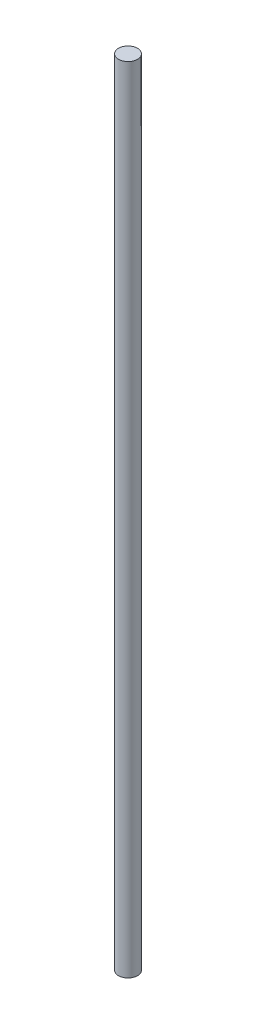
SolidWorks part; units mm, degrees
material "1.2343 (X38CrMoV5-1)"
ref_plane "Front Plane" through (0, 0, 0) normal (0, 0, 1) x (1, 0, 0)
ref_plane "Top Plane" through (0, 0, 0) normal (0, 1, 0) x (1, 0, 0)
ref_plane "Right Plane" through (0, 0, 0) normal (1, 0, 0) x (0, 0, -1)
sketch "Sketch1" plane through (0, 0, 0) normal (0, 1, 0) x (1, 0, 0)
  circle A0 centre (0, 0) radius 5
  dimension "D1" = 10
extrude "Boss-Extrude1" add sketch "Sketch1" along normal blind 416
